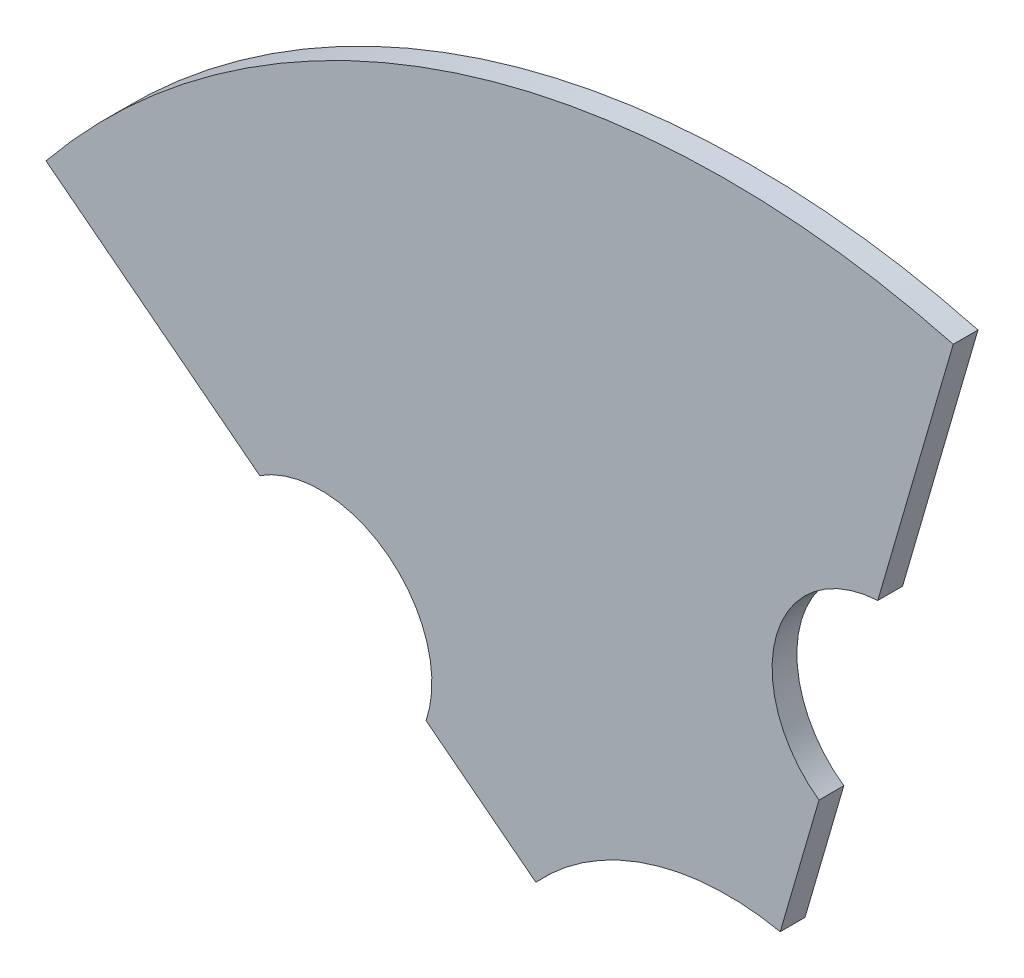
SolidWorks part; units mm, degrees
ref_plane "Front Plane" through (0, 0, 0) normal (0, 0, 1) x (1, 0, 0)
ref_plane "Top Plane" through (0, 0, 0) normal (0, 1, 0) x (1, 0, 0)
ref_plane "Right Plane" through (0, 0, 0) normal (1, 0, 0) x (0, 0, -1)
sketch "Sketch12" plane through (0, 0, 0) normal (0, 0, 1) x (1, 0, 0)
  line L0 (0, 38.1) -> (22.3946, 30.8235) construction
  line L1 (-5.8868, 18.1176) -> (15.4118, 11.1973) construction
  line L2 (4.7625, 14.6575) -> (11.1973, 34.4618) construction
  circle A0 centre (0, 0) radius 50.165
  circle A2 centre (-22.3946, 30.8235) radius 9.5631
  circle A3 centre (0, 38.1) radius 9.5631
  circle A4 centre (22.3946, 30.8235) radius 9.5631
  circle A5 centre (36.2353, 11.7735) radius 9.5631
  circle A6 centre (15.4118, 11.1973) radius 9.6393
  circle A7 centre (-5.8868, 18.1176) radius 9.6393
  circle A8 centre (0, 0) radius 8.255
  circle A9 centre (7.9799, 24.5596) radius 5.715
  point P18 (7.9799, 24.5596)
  dimension "D1" = 19.1262
  dimension "D2" = 16.51
  dimension "D3" = 100.33
  dimension "D4" = 19.2786
  dimension "D15" = 11.43
  dimension "D5" = 15.4118
  dimension "D6" = 22.3946
  dimension "D7" = 36.2353
  dimension "D8" = 5.8868
  dimension "D9" = 22.3946
  dimension "D10" = 11.1973
  dimension "D11" = 11.7735
  dimension "D12" = 18.1176
  dimension "D13" = 30.8235
  dimension "D14" = 38.1
sketch "Sketch13" plane through (0, 0, 0) normal (0, 0, 1) x (1, 0, 0)
  line L0 (11.5514, 43.5801) -> (2.6822, 13.0625)
  line L1 (-34.961, 28.4672) -> (-9.8479, 8.9912)
  circle A0 centre (0, 0) radius 13.335 construction
  circle A6 centre (0, 0) radius 8.255 construction
  circle A7 centre (0, 0) radius 8.255
  circle A8 centre (0, 0) radius 50.165 construction
  circle A9 centre (0, 0) radius 50.165
  arc A10 (2.6822, 13.0625) -> (-9.8479, 8.9912) centre (0, 0) ccw
  arc A11 (11.5514, 43.5801) -> (-34.961, 28.4672) centre (0, 0) ccw
  circle A12 centre (0, 0) radius 45.085 construction
  dimension "D3" = 2.6822
  dimension "D4" = 11.5514
  dimension "D5" = 9.8479
  dimension "D1" = 5.08
  dimension "D2" = 5.08
extrude "Boss-Extrude1" add sketch "Sketch13" against normal blind 1.27
sketch "Sketch14" plane through (0, 0, 0) normal (0, 0, 1) x (1, 0, 0)
  circle A0 centre (-22.3946, 30.8235) radius 1.27 construction
  circle A1 centre (0, 38.1) radius 1.27 construction
  circle A2 centre (-5.8868, 18.1176) radius 1.27 construction
  point P0 (-22.3946, 30.8235)
  point P1 (0, 38.1)
  point P3 (-5.8868, 18.1176)
  dimension "D1" = 2.54
  dimension "D2" = 2.54
  dimension "D3" = 2.54
sketch "Sketch15" plane through (0, 0, 0) normal (0, 0, 1) x (1, 0, 0)
  line L0 (11.5514, 43.5801) -> (2.6822, 13.0625) construction
  line L1 (7.6823, 30.2669) -> (4.6696, 19.9009)
  line L2 (0, 0) -> (-13.932, 42.8784) construction
  line L3 (-24.0055, 19.9709) -> (-15.4753, 13.3554)
  circle A0 centre (7.9799, 24.5596) radius 5.715 construction
  arc A1 (7.6823, 30.2669) -> (4.6696, 19.9009) centre (7.9799, 24.5596) ccw
  arc A2 (11.5514, 43.5801) -> (-34.961, 28.4672) centre (0, 0) ccw construction
  arc A3 (-24.0055, 19.9709) -> (-15.4753, 13.3554) centre (-20.8917, 15.1787) cw
extrude "Cut-Extrude1" cut sketch "Sketch15" against normal through all
